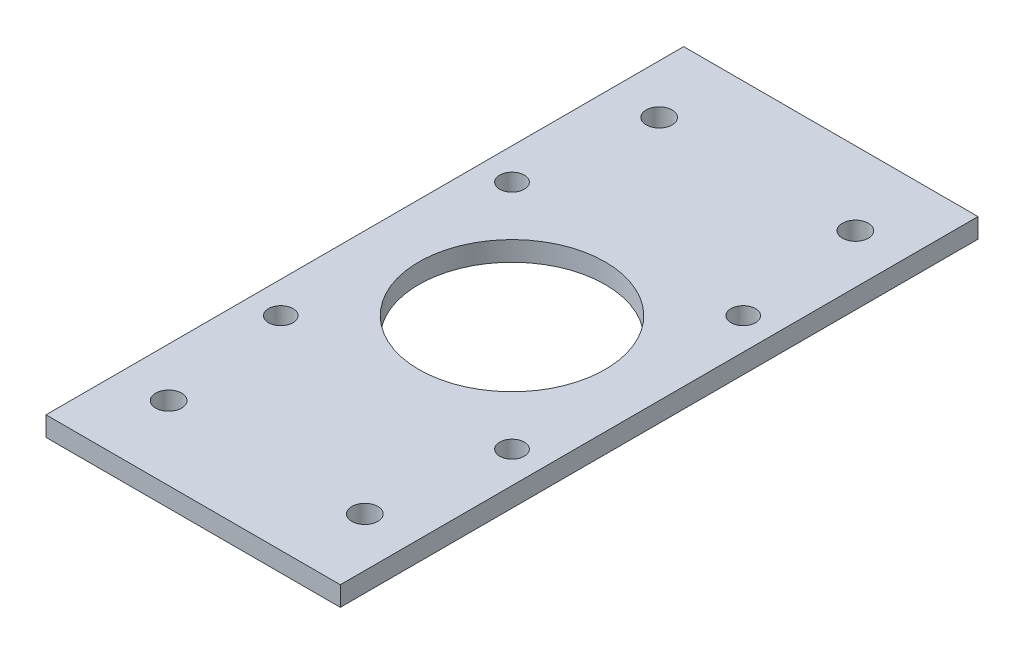
SolidWorks part; units mm, degrees
material "Liga 1060"
ref_plane "Plano frontal" through (0, 0, 0) normal (0, 0, 1) x (1, 0, 0)
ref_plane "Plano superior" through (0, 0, 0) normal (0, 1, 0) x (1, 0, 0)
ref_plane "Plano direito" through (0, 0, 0) normal (1, 0, 0) x (0, 0, -1)
sketch "Esboço1" plane through (0, 0, 0) normal (0, 1, 0) x (1, 0, 0)
  line L1 (-30, -65) -> (30, -65)
  line L2 (-30, -65) -> (-30, 65)
  line L3 (-30, 65) -> (30, 65)
  line L4 (30, -65) -> (30, 65)
  line L5 (-30, -65) -> (30, 65) construction
  line L6 (-30, 65) -> (30, -65) construction
  point P0 (0, 0)
  dimension "D1" = 60
  dimension "D2" = 130
extrude "Ressalto-extrusão1" add sketch "Esboço1" along normal blind 4
sketch "Esboço2" plane through (0, 4, 0) normal (0, 1, 0) x (1, 0, 0)
  line L1 (-23.57, -23.57) -> (23.57, -23.57) construction
  line L2 (-23.57, -23.57) -> (-23.57, 23.57) construction
  line L3 (-23.57, 23.57) -> (23.57, 23.57) construction
  line L4 (23.57, -23.57) -> (23.57, 23.57) construction
  line L5 (-23.57, -23.57) -> (23.57, 23.57) construction
  line L6 (-23.57, 23.57) -> (23.57, -23.57) construction
  circle A0 centre (0, 0) radius 19
  circle A1 centre (-23.57, 23.57) radius 2.5
  circle A2 centre (23.57, 23.57) radius 2.5
  circle A3 centre (23.57, -23.57) radius 2.5
  circle A4 centre (-23.57, -23.57) radius 2.5
  dimension "D1" = 38
  dimension "D2" = 5
  dimension "D3" = 47.14
extrude "Corte-extrusão1" cut sketch "Esboço2" against normal through all
hole_wizard "Furo com folga de M51" positions "Esboço3" profile "Esboço4" hole size "M5" standard "Ansi Metric" end condition through all
sketch "Esboço3" plane through (0, 4, 0) normal (0, 1, 0) x (1, 0, 0)
  line L0 (-30, -65) -> (30, -65) construction
  line L1 (30, 65) -> (-30, 65) construction
  line L2 (30, -65) -> (30, 65) construction
  line L3 (-30, 65) -> (-30, -65) construction
  point P0 (-20, -50)
  point P2 (20, -50)
  point P4 (-20, 50)
  point P6 (20, 50)
  dimension "D1" = 15
  dimension "D2" = 15
  dimension "D3" = 10
  dimension "D4" = 10
sketch "Esboço4" plane through (-20, 4, 50) normal (1, 0, 0) x (0, 0, 1)
  line L0 (0, 0) -> (0, 4)
  line L1 (0, 4) -> (2.65, 4)
  line L2 (2.65, 4) -> (2.65, 0)
  line L5 (2.65, 0) -> (0, 0)
  line L11 (0, -6.35) -> (0, 107.95) construction
  dimension "Thru Hole Dia." = 5.3
  dimension "Thru Hole Depth" = 4
